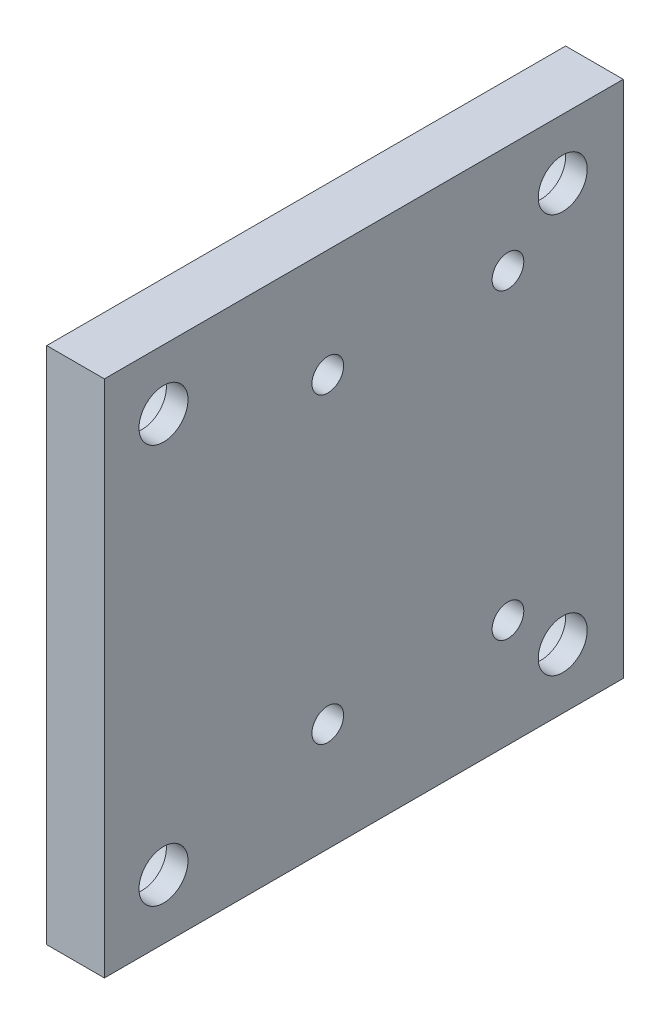
SolidWorks part; units mm, degrees
ref_plane "Alzado" through (0, 0, 0) normal (0, 0, 1) x (1, 0, 0)
ref_plane "Planta" through (0, 0, 0) normal (0, 1, 0) x (1, 0, 0)
ref_plane "Vista lateral" through (0, 0, 0) normal (1, 0, 0) x (0, 0, -1)
ref_plane "Plano1" through (-12.9, 0, 0) normal (1, 0, 0) x (0, 0, -1)
sketch "Croquis1" plane through (-12.9, 0, 0) normal (1, 0, 0) x (0, 0, -1)
  line L0 (-76.5, -18) -> (-76.5, 18)
  line L1 (-76.5, 18) -> (-112.5, 18)
  line L2 (-112.5, 18) -> (-112.5, -18)
  line L3 (-112.5, -18) -> (-76.5, -18)
extrude "Saliente-Extruir1" add sketch "Croquis1" along normal blind 4
ref_plane "Plano2" through (-13.9, 0, 0) normal (1, 0, 0) x (0, 0, -1)
sketch "Croquis2" plane through (-13.9, 0, 0) normal (1, 0, 0) x (0, 0, -1)
  circle A0 centre (-80.7, -13.85) radius 1.7
  circle A1 centre (-108.4, -13.85) radius 1.7
  circle A2 centre (-80.7, 13.85) radius 1.7
  circle A3 centre (-108.4, 13.85) radius 1.7
extrude "Cortar-Extruir1" cut sketch "Croquis2" along normal blind 6
ref_plane "Plano3" through (-13.9, 0, 0) normal (1, 0, 0) x (0, 0, -1)
sketch "Croquis3" plane through (-13.9, 0, 0) normal (1, 0, 0) x (0, 0, -1)
  circle A0 centre (-80.7, -13.85) radius 3.1
  circle A1 centre (-108.4, -13.85) radius 3.1
  circle A2 centre (-80.7, 13.85) radius 3.1
  circle A3 centre (-108.4, 13.85) radius 3.1
extrude "Cortar-Extruir2" cut sketch "Croquis3" along normal blind 3.5
ref_plane "Plano4" through (-13.9, 0, 0) normal (1, 0, 0) x (0, 0, -1)
sketch "Croquis4" plane through (-13.9, 0, 0) normal (1, 0, 0) x (0, 0, -1)
  circle A0 centre (-97, -10.5) radius 1.1
  circle A1 centre (-84.5, -10.5) radius 1.1
  circle A2 centre (-97, 10.5) radius 1.1
  circle A3 centre (-84.5, 10.5) radius 1.1
extrude "Cortar-Extruir3" cut sketch "Croquis4" along normal blind 6
